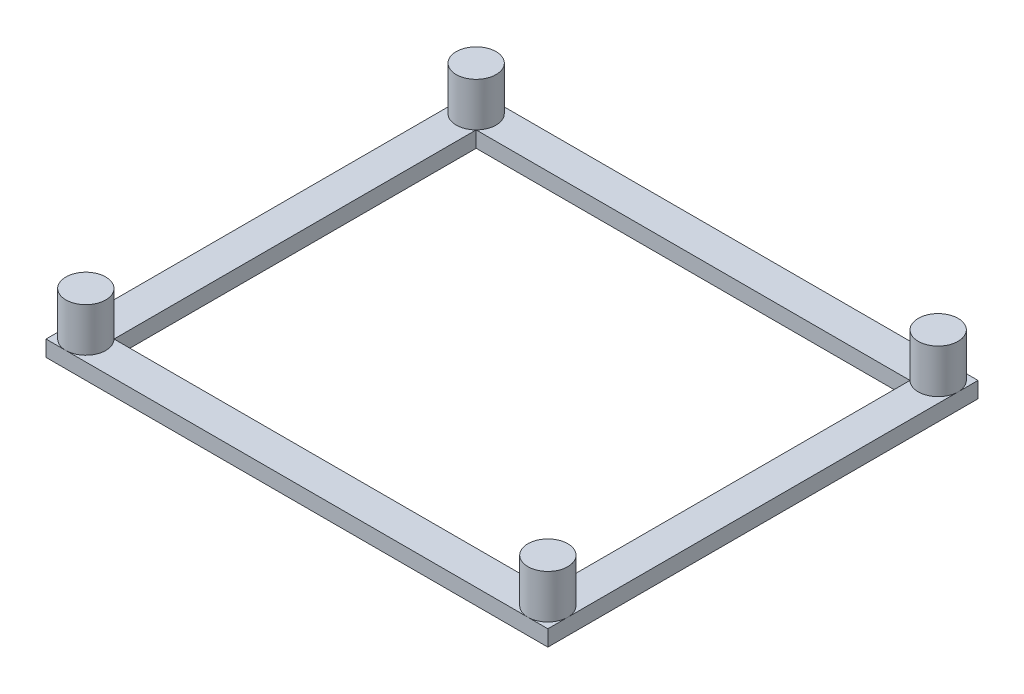
SolidWorks part; units mm, degrees
ref_plane "Front Plane" through (0, 0, 0) normal (0, 0, 1) x (1, 0, 0)
ref_plane "Top Plane" through (0, 0, 0) normal (0, 1, 0) x (1, 0, 0)
ref_plane "Right Plane" through (0, 0, 0) normal (1, 0, 0) x (0, 0, -1)
sketch "Sketch4" plane through (0, 0, 0) normal (0, 1, 0) x (1, 0, 0)
  line L0 (0, 49) -> (58, 49) construction
  line L1 (58, 49) -> (58, 0) construction
  line L2 (58, 0) -> (0, 0) construction
  line L3 (0, 0) -> (0, 49) construction
  circle A4 centre (0, 0) radius 1.8415
  circle A5 centre (58, 0) radius 1.8415
  circle A6 centre (58, 49) radius 1.8415
  circle A7 centre (0, 49) radius 1.8415
  circle A8 centre (0, 49) radius 2.5
  circle A9 centre (0, 0) radius 2.5
  circle A10 centre (58, 0) radius 2.5
  circle A11 centre (58, 49) radius 2.5
  dimension "D1" = 5
  dimension "D2" = 49
  dimension "D3" = 58
extrude "Boss-Extrude4" add sketch "Sketch4" along normal blind 7.5 separate body contours A10 A5 | A5 | A9 A4 | A4 | A8 A7 | A7 | A6 | A11 A6
sketch "Sketch5" plane through (0, 0, 0) normal (0, -1, 0) x (1, 0, 0)
  line L0 (0, -49) -> (-2.5, -51.5) construction
  line L1 (-2.5, 2.5) -> (60.5, 2.5)
  line L2 (-2.5, 2.5) -> (-2.5, -51.5)
  line L3 (-2.5, -51.5) -> (60.5, -51.5)
  line L4 (60.5, 2.5) -> (60.5, -51.5)
  line L5 (1.7678, -47.2322) -> (1.7678, -1.7678)
  line L6 (1.7678, -1.7678) -> (56.2322, -1.7678)
  line L7 (1.7678, -47.2322) -> (56.2322, -47.2322)
  line L8 (56.2322, -1.7678) -> (56.2322, -47.2322)
  line L9 (0, -49) -> (1.7678, -47.2322) construction
  circle A0 centre (58, -49) radius 2.5 construction
  circle A2 centre (0, -49) radius 2.5 construction
  circle A3 centre (58, 0) radius 2.5 construction
  circle A4 centre (0, 0) radius 2.5 construction
extrude "Boss-Extrude5" add sketch "Sketch5" against normal blind 2
